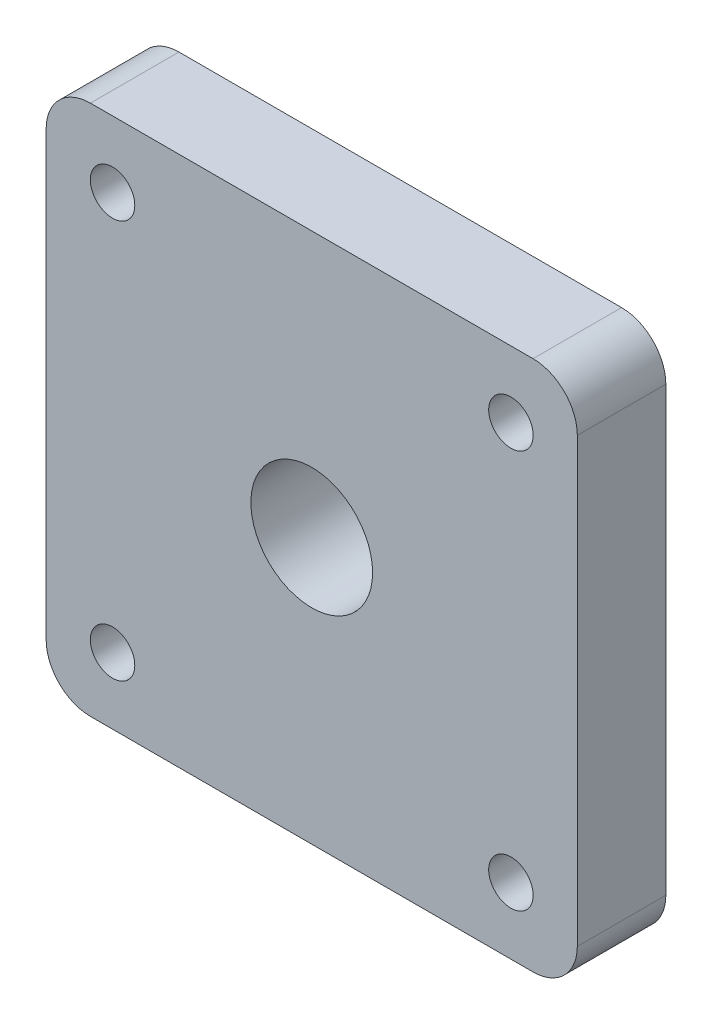
SolidWorks part; units mm, degrees
material "Plain Carbon Steel"
ref_plane "Front Plane" through (0, 0, 0) normal (0, 0, 1) x (1, 0, 0)
ref_plane "Top Plane" through (0, 0, 0) normal (0, 1, 0) x (1, 0, 0)
ref_plane "Right Plane" through (0, 0, 0) normal (1, 0, 0) x (0, 0, -1)
sketch "Sketch1" plane through (0, 0, 0) normal (0, 0, 1) x (1, 0, 0)
  line L1 (-31.75, 38.1) -> (31.75, 38.1)
  line L2 (-38.1, 31.75) -> (-38.1, -31.75)
  line L3 (-31.75, -38.1) -> (31.75, -38.1)
  line L4 (38.1, 31.75) -> (38.1, -31.75)
  line L5 (-38.1, 38.1) -> (38.1, -38.1) construction
  line L6 (-38.1, -38.1) -> (38.1, 38.1) construction
  line L7 (-28.575, 28.575) -> (28.575, 28.575) construction
  line L8 (-28.575, 28.575) -> (-28.575, -28.575) construction
  line L9 (-28.575, -28.575) -> (28.575, -28.575) construction
  line L10 (28.575, 28.575) -> (28.575, -28.575) construction
  line L11 (-28.575, 28.575) -> (28.575, -28.575) construction
  line L12 (-28.575, -28.575) -> (28.575, 28.575) construction
  circle A0 centre (0, 0) radius 8.7312
  circle A1 centre (-28.575, 28.575) radius 3.1877
  circle A2 centre (28.575, 28.575) radius 3.1877
  circle A3 centre (28.575, -28.575) radius 3.1877
  circle A4 centre (-28.575, -28.575) radius 3.1877
  arc A5 (-38.1, -31.75) -> (-31.75, -38.1) centre (-31.75, -31.75) ccw
  arc A6 (31.75, -38.1) -> (38.1, -31.75) centre (31.75, -31.75) ccw
  arc A7 (31.75, 38.1) -> (38.1, 31.75) centre (31.75, 31.75) cw
  arc A8 (-31.75, 38.1) -> (-38.1, 31.75) centre (-31.75, 31.75) ccw
  dimension "D3" = 17.4625
  dimension "D4" = 6.3754
  dimension "D5" = 6.3754
  dimension "D6" = 6.3754
  dimension "D7" = 6.3754
  dimension "D9" = 6.35
  dimension "D1" = 76.2
  dimension "D2" = 76.2
  dimension "D8" = 9.525
extrude "Boss-Extrude1" add sketch "Sketch1" along normal blind 12.7
scale "Scale1" scale about centroid uniform scaling yes scale factor 0.66
